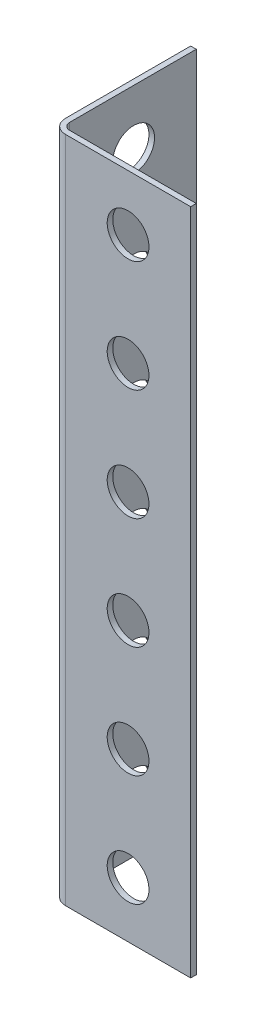
SolidWorks part; units mm, degrees
material "AISI 1020"
ref_plane "Front Plane" through (0, 0, 0) normal (0, 0, 1) x (1, 0, 0)
ref_plane "Top Plane" through (0, 0, 0) normal (0, 1, 0) x (1, 0, 0)
ref_plane "Right Plane" through (0, 0, 0) normal (1, 0, 0) x (0, 0, -1)
sketch "Sketch1" plane through (0, 0, 0) normal (0, 1, 0) x (1, 0, 0)
  line L0 (1.27, 30.48) -> (30.48, 30.48)
  line L1 (0, 0) -> (31.75, 0)
  line L2 (0, 0) -> (0, 31.75)
  line L3 (0, 31.75) -> (31.75, 31.75)
  line L4 (31.75, 0) -> (31.75, 31.75)
  line L5 (30.48, 1.27) -> (30.48, 30.48)
  line L6 (1.27, 1.27) -> (30.48, 1.27)
  line L7 (1.27, 1.27) -> (1.27, 30.48)
  line L8 (1.27, 30.48) -> (1.27, 31.75)
  line L9 (30.48, 1.27) -> (31.75, 1.27)
  dimension "D1" = 31.75
  dimension "D2" = 31.75
  dimension "D3" = 1.27
extrude "Boss-Extrude1" add sketch "Sketch1" along normal blind 1219.2 contours L9 L6 L7 L8 L3 L2 L1 L4
sketch "Sketch3" plane through (0, 0, 0) normal (-1, 0, 0) x (0, 0, 1)
  line L0 (-17.4625, 0) -> (-17.4625, 12.7) construction
  line L2 (-31.75, 1219.2) -> (-31.75, 0) construction
  circle A0 centre (-17.4625, 12.7) radius 4.7625
  circle A1 centre (-17.4625, 38.1) radius 4.7625
  circle A2 centre (-17.4625, 63.5) radius 4.7625
  circle A3 centre (-17.4625, 88.9) radius 4.7625
  circle A4 centre (-17.4625, 114.3) radius 4.7625
  circle A5 centre (-17.4625, 139.7) radius 4.7625
  circle A6 centre (-17.4625, 165.1) radius 4.7625
  circle A7 centre (-17.4625, 190.5) radius 4.7625
  circle A8 centre (-17.4625, 215.9) radius 4.7625
  circle A9 centre (-17.4625, 241.3) radius 4.7625
  circle A10 centre (-17.4625, 266.7) radius 4.7625
  circle A11 centre (-17.4625, 292.1) radius 4.7625
  circle A12 centre (-17.4625, 317.5) radius 4.7625
  circle A13 centre (-17.4625, 342.9) radius 4.7625
  circle A14 centre (-17.4625, 368.3) radius 4.7625
  circle A15 centre (-17.4625, 393.7) radius 4.7625
  circle A16 centre (-17.4625, 419.1) radius 4.7625
  circle A17 centre (-17.4625, 444.5) radius 4.7625
  circle A18 centre (-17.4625, 469.9) radius 4.7625
  circle A19 centre (-17.4625, 495.3) radius 4.7625
  circle A20 centre (-17.4625, 520.7) radius 4.7625
  circle A21 centre (-17.4625, 546.1) radius 4.7625
  circle A22 centre (-17.4625, 571.5) radius 4.7625
  circle A23 centre (-17.4625, 596.9) radius 4.7625
  circle A24 centre (-17.4625, 622.3) radius 4.7625
  circle A25 centre (-17.4625, 647.7) radius 4.7625
  circle A26 centre (-17.4625, 673.1) radius 4.7625
  circle A27 centre (-17.4625, 698.5) radius 4.7625
  circle A28 centre (-17.4625, 723.9) radius 4.7625
  circle A29 centre (-17.4625, 749.3) radius 4.7625
  circle A30 centre (-17.4625, 774.7) radius 4.7625
  circle A31 centre (-17.4625, 800.1) radius 4.7625
  circle A32 centre (-17.4625, 825.5) radius 4.7625
  circle A33 centre (-17.4625, 850.9) radius 4.7625
  circle A34 centre (-17.4625, 876.3) radius 4.7625
  circle A35 centre (-17.4625, 901.7) radius 4.7625
  circle A36 centre (-17.4625, 927.1) radius 4.7625
  circle A37 centre (-17.4625, 952.5) radius 4.7625
  circle A38 centre (-17.4625, 977.9) radius 4.7625
  circle A39 centre (-17.4625, 1003.3) radius 4.7625
  circle A40 centre (-17.4625, 1028.7) radius 4.7625
  circle A41 centre (-17.4625, 1054.1) radius 4.7625
  circle A42 centre (-17.4625, 1079.5) radius 4.7625
  circle A43 centre (-17.4625, 1104.9) radius 4.7625
  circle A44 centre (-17.4625, 1130.3) radius 4.7625
  circle A45 centre (-17.4625, 1155.7) radius 4.7625
  circle A46 centre (-17.4625, 1181.1) radius 4.7625
  circle A47 centre (-17.4625, 1206.5) radius 4.7625
  dimension "D1" = 9.525
  dimension "D2" = 12.7
  dimension "D4" = 14.2875
  dimension "D3" = 48
extrude "Cut-Extrude1" cut sketch "Sketch3" against normal up to next (1.27 mm away)
sketch "Sketch4" plane through (0, 0, 0) normal (0, 0, 1) x (1, 0, 0)
  line L0 (17.4625, 1219.2) -> (17.4625, 1206.5) construction
  line L2 (31.75, 1219.2) -> (31.75, 0) construction
  circle A0 centre (17.4625, 1206.5) radius 4.7625
  circle A1 centre (17.4625, 1181.1) radius 4.7625
  circle A2 centre (17.4625, 1155.7) radius 4.7625
  circle A3 centre (17.4625, 1130.3) radius 4.7625
  circle A4 centre (17.4625, 1104.9) radius 4.7625
  circle A5 centre (17.4625, 1079.5) radius 4.7625
  circle A6 centre (17.4625, 1054.1) radius 4.7625
  circle A7 centre (17.4625, 1028.7) radius 4.7625
  circle A8 centre (17.4625, 1003.3) radius 4.7625
  circle A9 centre (17.4625, 977.9) radius 4.7625
  circle A10 centre (17.4625, 952.5) radius 4.7625
  circle A11 centre (17.4625, 927.1) radius 4.7625
  circle A12 centre (17.4625, 901.7) radius 4.7625
  circle A13 centre (17.4625, 876.3) radius 4.7625
  circle A14 centre (17.4625, 850.9) radius 4.7625
  circle A15 centre (17.4625, 825.5) radius 4.7625
  circle A16 centre (17.4625, 800.1) radius 4.7625
  circle A17 centre (17.4625, 774.7) radius 4.7625
  circle A18 centre (17.4625, 749.3) radius 4.7625
  circle A19 centre (17.4625, 723.9) radius 4.7625
  circle A20 centre (17.4625, 698.5) radius 4.7625
  circle A21 centre (17.4625, 673.1) radius 4.7625
  circle A22 centre (17.4625, 647.7) radius 4.7625
  circle A23 centre (17.4625, 622.3) radius 4.7625
  circle A24 centre (17.4625, 596.9) radius 4.7625
  circle A25 centre (17.4625, 571.5) radius 4.7625
  circle A26 centre (17.4625, 546.1) radius 4.7625
  circle A27 centre (17.4625, 520.7) radius 4.7625
  circle A28 centre (17.4625, 495.3) radius 4.7625
  circle A29 centre (17.4625, 469.9) radius 4.7625
  circle A30 centre (17.4625, 444.5) radius 4.7625
  circle A31 centre (17.4625, 419.1) radius 4.7625
  circle A32 centre (17.4625, 393.7) radius 4.7625
  circle A33 centre (17.4625, 368.3) radius 4.7625
  circle A34 centre (17.4625, 342.9) radius 4.7625
  circle A35 centre (17.4625, 317.5) radius 4.7625
  circle A36 centre (17.4625, 292.1) radius 4.7625
  circle A37 centre (17.4625, 266.7) radius 4.7625
  circle A38 centre (17.4625, 241.3) radius 4.7625
  circle A39 centre (17.4625, 215.9) radius 4.7625
  circle A40 centre (17.4625, 190.5) radius 4.7625
  circle A41 centre (17.4625, 165.1) radius 4.7625
  circle A42 centre (17.4625, 139.7) radius 4.7625
  circle A43 centre (17.4625, 114.3) radius 4.7625
  circle A44 centre (17.4625, 88.9) radius 4.7625
  circle A45 centre (17.4625, 63.5) radius 4.7625
  circle A46 centre (17.4625, 38.1) radius 4.7625
  circle A47 centre (17.4625, 12.7) radius 4.7625
  dimension "D1" = 9.525
  dimension "D2" = 12.7
  dimension "D4" = 14.2875
  dimension "D3" = 48
extrude "Cut-Extrude2" cut sketch "Sketch4" against normal up to next (1.27 mm away)
fillet "Fillet1" radius 3.175 1 edges at (0, 609.6, 0)
fillet "Fillet2" radius 1.5875 1 edges at (1.27, 609.6, -1.27)
sketch "Sketch5" plane through (0, 1219.2, 0) normal (0, 1, 0) x (1, 0, 0)
  line L12 (0, 31.75) -> (0, 3.175)
  line L13 (3.175, 0) -> (31.75, 0)
  line L14 (31.75, 0) -> (31.75, 1.27)
  line L15 (31.75, 1.27) -> (2.8575, 1.27)
  line L16 (1.27, 2.8575) -> (1.27, 31.75)
  line L17 (1.27, 31.75) -> (0, 31.75)
  line L18 (0, 31.75) -> (0, 3.175)
  line L19 (3.175, 0) -> (31.75, 0)
  line L20 (31.75, 0) -> (31.75, 1.27)
  line L21 (31.75, 1.27) -> (2.8575, 1.27)
  line L22 (1.27, 2.8575) -> (1.27, 31.75)
  line L23 (1.27, 31.75) -> (0, 31.75)
  arc A4 (0, 3.175) -> (3.175, 0) centre (3.175, 3.175) ccw
  arc A5 (1.27, 2.8575) -> (2.8575, 1.27) centre (2.8575, 2.8575) ccw
  arc A6 (0, 3.175) -> (3.175, 0) centre (3.175, 3.175) ccw
  arc A7 (1.27, 2.8575) -> (2.8575, 1.27) centre (2.8575, 2.8575) ccw
  dimension "D1" = 0
extrude "Cut-Extrude3" cut sketch "Sketch5" against normal blind 1066.8
